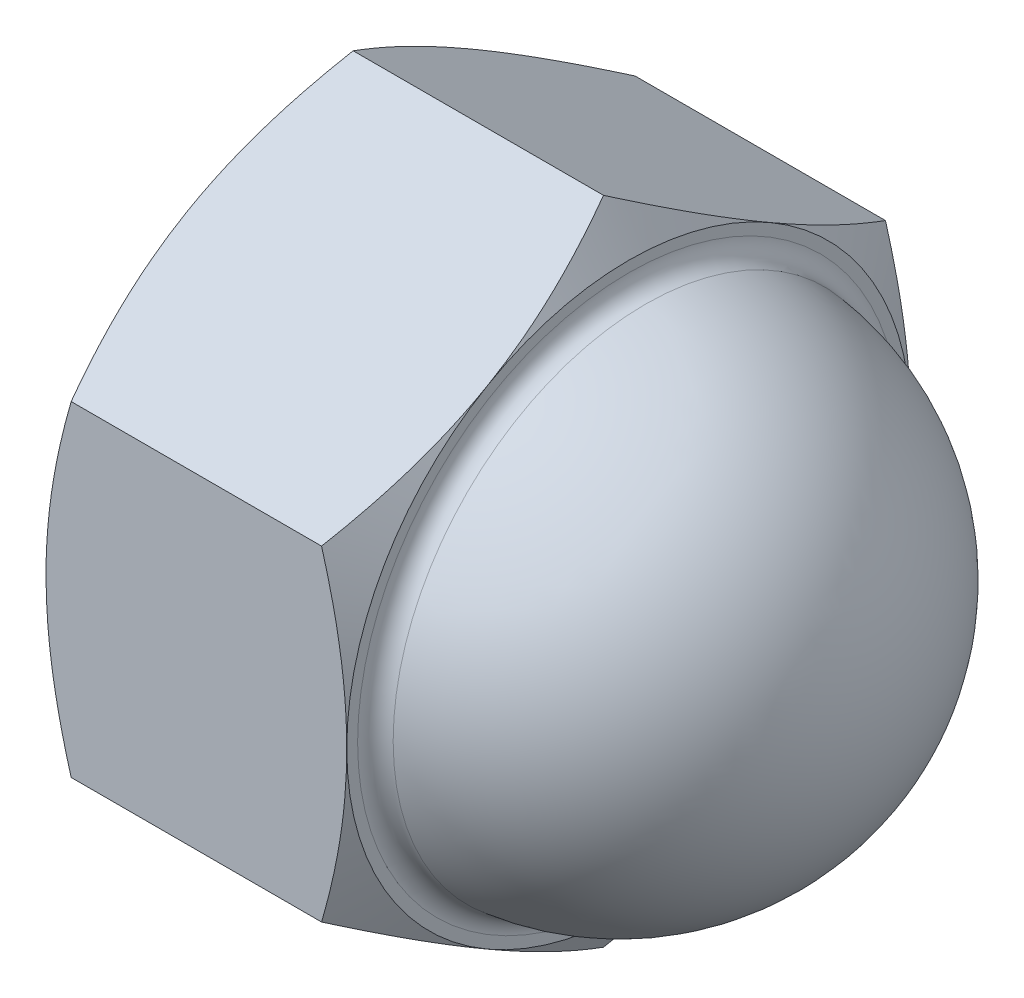
SolidWorks part; units mm, degrees
extrude "BaseNut" add sketch "BaseNutSke" along normal blind 16
sketch "BaseNutSke" plane through (0, 0, 0) normal (1, 0, 0) x (0, 0, -1)
  line L6 (15, 8.6603) -> (15, -8.6603)
  line L7 (-15, 8.6603) -> (-15, -8.6603)
  line L8 (15, 8.6603) -> (0, 17.3205)
  line L9 (0, 17.3205) -> (-15, 8.6603)
  line L10 (-15, -8.6603) -> (0, -17.3205)
  line L11 (0, -17.3205) -> (15, -8.6603)
  dimension "D4" = 60
  dimension "D1" = 120
  dimension "D2" = 15
  dimension "D3" = 15
  dimension "Width_flats" = 30
revolve "DoubleChamfer" cut sketch "Sketch4" angle 360 about L10
sketch "Sketch4" plane through (0, 0, 0) normal (0, 0, 1) x (1, 0, 0)
  line L0 (0, 15) -> (2.7831, 19.8205)
  line L1 (16, 15) -> (13.2169, 19.8205)
  line L2 (2.7831, 19.8205) -> (13.2169, 19.8205)
  line L3 (16, 15) -> (18, 15)
  line L4 (18, 15) -> (18, 30)
  line L5 (18, 30) -> (-2, 30)
  line L6 (0, 15) -> (-2, 15)
  line L7 (-2, 15) -> (-2, 30)
  line L8 (16, 17.3205) -> (16, 8.6603) construction
  line L9 (0, 17.3205) -> (0, 8.6603) construction
  line L10 (0, 0) -> (57.15, 0) construction
  line L11 (16, 17.3205) -> (0, 17.3205) construction
  point P17 (16, 15)
  dimension "D1" = 30
  dimension "D2" = 30
  dimension "D3" = 2
  dimension "D4" = 2
  dimension "D5" = 2.5
  dimension "D6" = 15
  dimension "D7" = 15
ref_plane "Plane1" through (0, 0, 0) normal (0, 0, 1) x (1, 0, 0)
ref_plane "Plane2" through (0, 0, 0) normal (0, 1, 0) x (1, 0, 0)
ref_plane "Plane3" through (0, 0, 0) normal (1, 0, 0) x (0, 0, -1)
sketch "DomeSke" plane through (0, 0, 0) normal (0, 0, 1) x (1, 0, 0)
  line L0 (0, 0) -> (63.5, 0) construction
  line L2 (29, 0) -> (27.4, 0)
  line L3 (0, 13.5) -> (15.5, 13.5)
  line L5 (0, 13.5) -> (0, 11.9)
  line L8 (0, 11.9) -> (15.5, 11.9)
  arc A0 (15.5, 13.5) -> (29, 0) centre (15.5, 0) cw
  arc A1 (15.5, 11.9) -> (27.4, 0) centre (15.5, 0) cw
  dimension "Dome_thk" = 1.6
revolve "Dome" add sketch "DomeSke" angle 360 about L0
sketch "TapDriSke" plane through (0, 0, 0) normal (0, 0, 1) x (1, 0, 0)
  line L0 (0, 0) -> (44.45, 0) construction
  line L1 (0, 8.75) -> (21.4, 8.75)
  line L2 (0, 12.9904) -> (0, 0) construction
  line L3 (21.4, 8.75) -> (26.6575, 0)
  line L4 (0, 0) -> (63.5, 0) construction
  line L5 (26.6575, 0) -> (0, 0)
  line L6 (0, 0) -> (0, 8.75)
  line L7 (21.4, -8.75) -> (26.6575, 0) construction
  line L8 (0, -8.75) -> (21.4, -8.75) construction
  line L9 (0.5, 6.35) -> (0.5, 3.175) construction
  dimension "Drill_depth" = 21.4
revolve "TapDrill" cut sketch "TapDriSke"
cosmetic thread "ThreadCosmetic" [suppressed]
revolve "EndChamfer" cut sketch "EndChamferSketch" angle 360 about L4
sketch "EndChamferSketch" plane through (0, 0, 0) normal (0, 0, 1) x (1, 0, 0)
  line L0 (-0.0746, 10) -> (0.0254, 10)
  line L1 (0.0254, 10) -> (0.9882, 8.625)
  line L2 (0.9882, 8.625) -> (-0.0746, 8.625)
  line L3 (-0.0746, 8.625) -> (-0.0746, 10)
  line L4 (0, 0) -> (-15.875, 0) construction
  line L5 (15.9746, 10) -> (16.1, 10)
  line L6 (16.1, 10) -> (16.1, 8.625)
  line L7 (16.1, 8.625) -> (15.0118, 8.625)
  line L8 (15.0118, 8.625) -> (15.9746, 10)
  line L9 (16, -12.9904) -> (16, 0) construction
  dimension "D1" = 0.1
  dimension "D2" = 35
  dimension "ChamferDepth" = 1.375
  dimension "D3" = 0.0254
  dimension "D4" = 35
  dimension "D5" = 0.1
  dimension "D6" = 0.0254
sketch "ThdSchSke" plane through (0, 0, 0) normal (0, 1, 0) x (1, 0, 0)
  line L0 (0.0381, 10) -> (-0.8372, 8.75)
  line L1 (-0.8372, 8.75) -> (-0.8372, 4.375)
  line L2 (-0.8372, 4.375) -> (0.9134, 4.375)
  line L3 (0.9134, 4.375) -> (0.9134, 8.75)
  line L4 (0.9134, 8.75) -> (0.0381, 10)
  line L5 (-38.1, 0) -> (3.175, 0) construction
  line L6 (0, 0) -> (-15.875, 0) construction
  line L7 (0, 0) -> (63.5, 0) construction
  line L9 (2.5381, 0.475) -> (2.5381, -5.875) construction
  dimension "D1" = 0.0381
  dimension "Thread_major" = 20
  dimension "Tap_drill" = 17.5
  dimension "OverCut" = 8.75
revolve "ThreadSchematic" [suppressed] cut sketch "ThdSchSke" angle 360 about L5
pattern_linear "ThdSchPat" [suppressed]
fillet "DomeFillet" radius 1 1 edges at (16, 0, 13.4907)
equation "' \"Width_flats@BaseNutSke\" = 30"
equation "' \"Hex_ht@BaseNut\" = 16"
equation "' \"Overall_ht@DomeSke\" = 29"
equation "' \"Dome_rad@DomeSke\" = 13.5"
equation "' \"Thread_min@TapDriSke\" = 17.5"
equation "' \"Drill_clr@TapDriSke\" = 1.0"
equation "' \"Advance@ThdSchSke\" = 2.5"
equation "' \"Thread_nominal@ThreadCosmetic\" = 20"
equation "' \"Radius@DomeFillet\" = 1.0"
equation "' \"Dome_thk@DomeSke\" = 1.6"
equation "\"Drill_depth@TapDriSke\" = \"Overall_ht@DomeSke\"  - \"Dome_thk@DomeSke\"- 0.3 * \"Thread_nominal@ThreadCosmetic\""
equation "\"Thread_depth@ThreadCosmetic\" = \"Thread_nominal@ThreadCosmetic\""
equation "\"D2@BaseNutSke\" = \"Width_flats@BaseNutSke\" / 2"
equation "\"D3@BaseNutSke\" = \"Width_flats@BaseNutSke\" / 2"
equation "\"D7@Sketch4\" = \"Width_flats@BaseNutSke\" / 2"
equation "\"D5@Sketch4\" = \"Width_flats@BaseNutSke\" / 12"
equation "\"Thread_major@ThdSchSke\" = \"Thread_nominal@ThreadCosmetic\""
equation "\"Tap_drill@ThdSchSke\" = \"Thread_min@TapDriSke\""
equation "\"OverCut@ThdSchSke\" = \"Tap_drill@ThdSchSke\" * 0.5"
equation "\"Num_threads@ThdSchPat\" = int(  ( \"Hex_ht@BaseNut\" - 0.002 ) / \"Advance@ThdSchSke\" + 0.999 )  + 1"
equation "' \"Num_threads@ThdSchPat\" = int(  ( \"Thread_depth@ThreadCosmetic\" - 0.002 ) / \"Advance@ThdSchSke\" + 0.999 )  + 1"
equation "\"Advance@ThdSchPat\" = ( \"Hex_ht@BaseNut\" - 0.002 ) /  (\"Num_threads@ThdSchPat\" - 1) 'relax it"
equation "' \"Advance@ThdSchPat\" = ( \"Thread_depth@ThreadCosmetic\" - 0.002 ) /  (\"Num_threads@ThdSchPat\" - 1) 'relax it"
equation "\"ThreadMajor@EndChamferSketch\" = \"Thread_nominal@ThreadCosmetic\" * 0.5"
equation "\"ChamferDepth@EndChamferSketch\" = (\"Thread_nominal@ThreadCosmetic\" - \"Thread_min@TapDriSke\") * 0.55"
